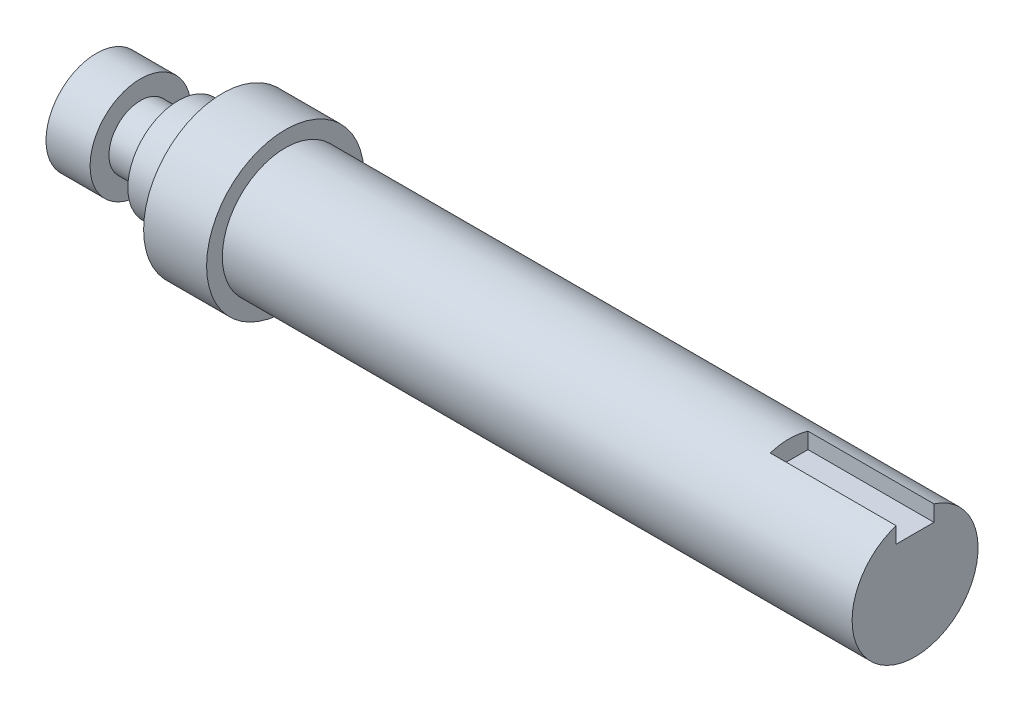
SolidWorks part; units mm, degrees
material "Ductile Iron"
ref_plane "Front Plane" through (0, 0, 0) normal (0, 0, 1) x (1, 0, 0)
ref_plane "Top Plane" through (0, 0, 0) normal (0, 1, 0) x (1, 0, 0)
ref_plane "Right Plane" through (0, 0, 0) normal (1, 0, 0) x (0, 0, -1)
sketch "Sketch1" plane through (0, 0, 0) normal (0, 0, 1) x (1, 0, 0)
  line L0 (-30.4262, 0) -> (36.8962, 0) construction
  line L1 (-65, 0) -> (-65, 8)
  line L2 (-65, 8) -> (-58, 8)
  line L3 (-58, 8) -> (-58, 5)
  line L4 (-58, 5) -> (-52, 5)
  line L5 (-52, 5) -> (-52, 8)
  line L6 (-52, 8) -> (-45, 8)
  line L7 (-45, 8) -> (-45, 12.5)
  line L8 (-45, 12.5) -> (-35, 12.5)
  line L9 (-35, 12.5) -> (-35, 10)
  line L10 (-35, 10) -> (65, 10)
  line L11 (65, 10) -> (65, 0)
  line L12 (65, 0) -> (-65, 0)
  point P15 (0, 0)
  dimension "D1" = 8
  dimension "D2" = 7
  dimension "D3" = 7
  dimension "D4" = 6
  dimension "D5" = 3
  dimension "D6" = 3
  dimension "D7" = 10
  dimension "D8" = 100
  dimension "D9" = 10
  dimension "D10" = 12.5
revolve "Revolve1" add sketch "Sketch1" angle 360 about L0
sketch "Sketch2" plane through (65, 0, 0) normal (1, 0, 0) x (0, 0, -1)
  line L0 (0, 0) -> (0, 13.3763) construction
  line L1 (-3, 9.5394) -> (-3, 7)
  line L2 (-3, 7) -> (3, 7)
  line L3 (3, 7) -> (3, 9.5394)
  circle A0 centre (0, 0) radius 10 construction
  arc A1 (3, 9.5394) -> (-3, 9.5394) centre (0, 0) ccw
  point P11 (0, 0)
  dimension "D1" = 6
  dimension "D2" = 7
extrude "Cut-Extrude1" cut sketch "Sketch2" against normal blind 20
